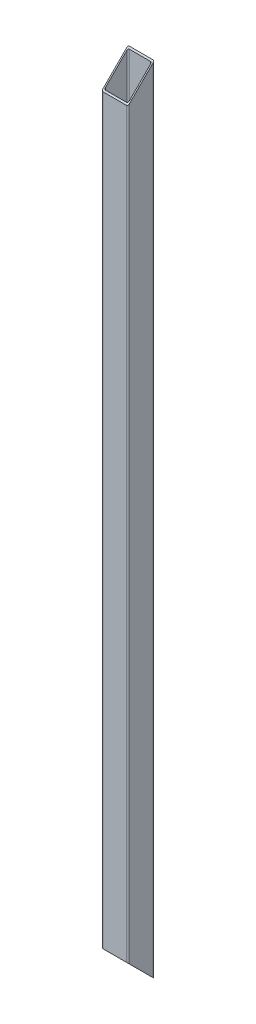
SolidWorks part; units mm, degrees
ref_plane "Płaszczyzna przednia" through (0, 0, 0) normal (0, 0, 1) x (1, 0, 0)
ref_plane "Płaszczyzna górna" through (0, 0, 0) normal (0, 1, 0) x (1, 0, 0)
ref_plane "Płaszczyzna prawa" through (0, 0, 0) normal (1, 0, 0) x (0, 0, -1)
sketch "Szkic1" plane through (0, 0, 0) normal (0, 1, 0) x (1, 0, 0)
  line L0 (3, 6) -> (3, 54)
  line L1 (3, 0) -> (57, 0)
  line L2 (0, 3) -> (0, 57)
  line L3 (3, 60) -> (57, 60)
  line L4 (60, 3) -> (60, 57)
  line L5 (0, 0) -> (42.6554, 0)
  line L6 (0, 0) -> (0, 31.4913)
  line L7 (6, 57) -> (54, 57)
  line L8 (57, 6) -> (57, 54)
  line L9 (6, 3) -> (54, 3)
  arc A0 (57, 60) -> (60, 57) centre (57, 57) cw
  arc A1 (54, 57) -> (57, 54) centre (54, 54) cw
  arc A2 (57, 0) -> (60, 3) centre (57, 3) ccw
  arc A3 (57, 6) -> (54, 3) centre (54, 6) cw
  arc A4 (3, 6) -> (6, 3) centre (6, 6) ccw
  arc A5 (3, 0) -> (0, 3) centre (3, 3) cw
  arc A6 (3, 54) -> (6, 57) centre (6, 54) cw
  arc A7 (0, 57) -> (3, 60) centre (3, 57) cw
  dimension "D1" = 3
extrude "Dodanie-wyciągnięcie1" add sketch "Szkic1" along normal blind 1810 contours A7 L2 A5 L1 A2 L4 A0 L3 L0 A6 L7 A1 L8 A3 L9 A4
ref_plane "Płaszczyzna1" through (0, 875, 875) normal (0, 0.7071, 0.7071) x (1, 0, 0)
sketch "Szkic2" plane through (0, 875, 875) normal (0, 0.7071, 0.7071) x (1, 0, 0)
  line L1 (117.6032, 1231.4878) -> (-55.0816, 1231.4878)
  line L2 (117.6032, 1231.4878) -> (117.6032, 1336.028)
  line L3 (117.6032, 1336.028) -> (-55.0816, 1336.028)
  line L4 (-55.0816, 1231.4878) -> (-55.0816, 1336.028)
extrude "Wytnij-wyciągnięcie1" cut sketch "Szkic2" along normal through all contours L2 L3 L4 L1
ref_plane "Płaszczyzna2" through (0, 30, -30) normal (0, -0.7071, 0.7071) x (1, 0, 0)
sketch "Szkic3" plane through (0, 30, -30) normal (0, -0.7071, 0.7071) x (1, 0, 0)
  line L1 (-67.1893, 62.3222) -> (110.4395, 62.3222)
  line L2 (-67.1893, 62.3222) -> (-67.1893, -58.2408)
  line L3 (-67.1893, -58.2408) -> (110.4395, -58.2408)
  line L4 (110.4395, 62.3222) -> (110.4395, -58.2408)
extrude "Wytnij-wyciągnięcie2" cut sketch "Szkic3" along normal through all contours L1 L4 L3 L2
